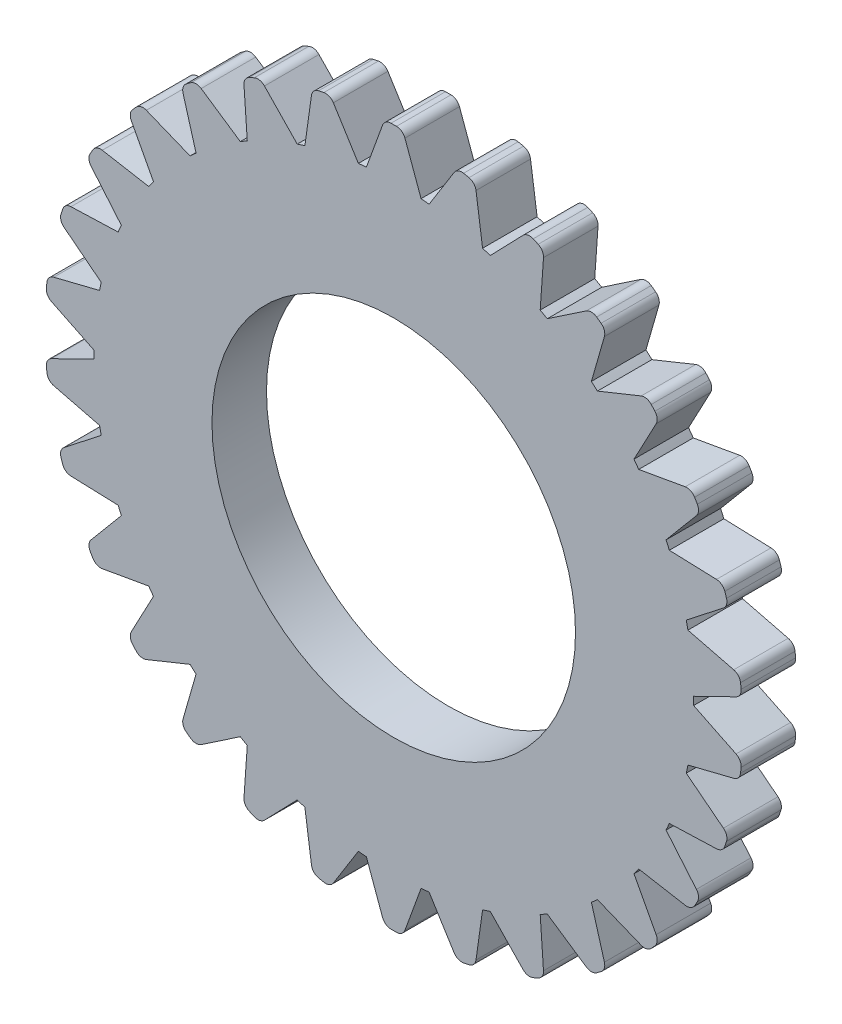
SolidWorks part; units mm, degrees
ref_plane "Front Plane" through (0, 0, 0) normal (0, 0, 1) x (1, 0, 0)
ref_plane "Top Plane" through (0, 0, 0) normal (0, 1, 0) x (1, 0, 0)
ref_plane "Right Plane" through (0, 0, 0) normal (1, 0, 0) x (0, 0, -1)
sketch "Sketch1" plane through (0, 0, 0) normal (0, 0, 1) x (1, 0, 0)
  circle A0 centre (0, 0) radius 16.5
  circle A1 centre (0, 0) radius 10
extrude "Boss-Extrude1" add sketch "Sketch1" along normal mid plane 3
sketch "Sketch3" plane through (0, 0, 1.5) normal (0, 0, 1) x (1, 0, 0)
  line L0 (0, 0) -> (0, 20.027) construction
  line L1 (-1.504, 16.4313) -> (-0.6163, 18.8704)
  line L2 (1.504, 16.4313) -> (0.6163, 18.8704)
  arc A0 (-0.1503, 19.1994) -> (0.1503, 19.1994) centre (0, 0) cw
  arc A1 (-0.6163, 18.8704) -> (-0.1503, 19.1994) centre (-0.1464, 18.6994) cw
  circle A2 centre (0, 0) radius 16.5 construction
  arc A3 (0.6163, 18.8704) -> (0.1503, 19.1994) centre (0.1464, 18.6994) ccw
  arc A4 (1.504, 16.4313) -> (-1.504, 16.4313) centre (0, 0) ccw
  point P13 (0, 19.2)
  dimension "D2" = 0.5
extrude "Boss-Extrude2" add sketch "Sketch3" against normal blind 3
pattern_circular "CirPattern1" count 30 over 360 about axis through (0, 0, 0) along (0, 0, 1) of "Boss-Extrude2"
